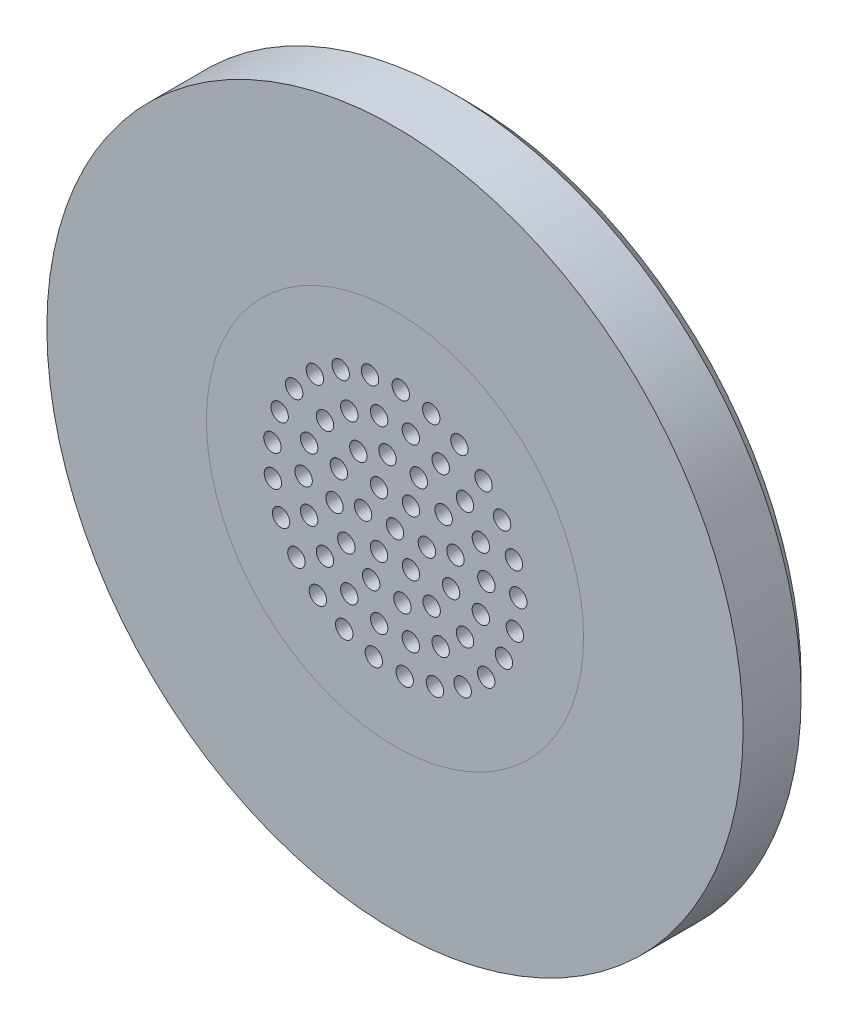
SolidWorks part; units mm, degrees
material "AISI 304"
ref_plane "Piano frontale" through (0, 0, 0) normal (0, 0, 1) x (1, 0, 0)
ref_plane "Piano superiore" through (0, 0, 0) normal (0, 1, 0) x (1, 0, 0)
ref_plane "Piano destro" through (0, 0, 0) normal (1, 0, 0) x (0, 0, -1)
sketch "Schizzo1" plane through (0, 0, 0) normal (0, 0, 1) x (1, 0, 0)
  line L0 (0, 0) -> (-24, 0) construction
  line L1 (0, 0) -> (-3.8661, 1.6411) construction
  line L2 (0, 0) -> (-8.4487, 0.9325) construction
  circle A0 centre (0, 0) radius 24
  circle A1 centre (-2.2, 0) radius 0.6
  circle A2 centre (0, 0) radius 2.2 construction
  circle A3 centre (0, 0) radius 4.2 construction
  circle A4 centre (0, 0) radius 0.6
  circle A5 centre (-3.8661, 1.6411) radius 0.6
  circle A6 centre (-1.1, 1.9053) radius 0.6
  circle A7 centre (1.1, 1.9053) radius 0.6
  circle A8 centre (2.2, 0) radius 0.6
  circle A9 centre (1.1, -1.9053) radius 0.6
  circle A10 centre (-1.1, -1.9053) radius 0.6
  circle A11 centre (-2.5276, 3.3543) radius 0.6
  circle A12 centre (-0.5119, 4.1687) radius 0.6
  circle A13 centre (1.6411, 3.8661) radius 0.6
  circle A14 centre (3.3543, 2.5276) radius 0.6
  circle A15 centre (4.1687, 0.5119) radius 0.6
  circle A16 centre (3.8661, -1.6411) radius 0.6
  circle A17 centre (2.5276, -3.3543) radius 0.6
  circle A18 centre (0.5119, -4.1687) radius 0.6
  circle A19 centre (-1.6411, -3.8661) radius 0.6
  circle A20 centre (-3.3543, -2.5276) radius 0.6
  circle A21 centre (-4.1687, -0.5119) radius 0.6
  circle A22 centre (0, 0) radius 6.3 construction
  circle A23 centre (-6.3, 0) radius 0.6
  circle A24 centre (-5.9201, 2.1547) radius 0.6
  circle A25 centre (-4.8261, 4.0496) radius 0.6
  circle A26 centre (-3.15, 5.456) radius 0.6
  circle A27 centre (-1.094, 6.2043) radius 0.6
  circle A28 centre (1.094, 6.2043) radius 0.6
  circle A29 centre (3.15, 5.456) radius 0.6
  circle A30 centre (4.8261, 4.0496) radius 0.6
  circle A31 centre (5.9201, 2.1547) radius 0.6
  circle A32 centre (6.3, 0) radius 0.6
  circle A33 centre (5.9201, -2.1547) radius 0.6
  circle A34 centre (4.8261, -4.0496) radius 0.6
  circle A35 centre (3.15, -5.456) radius 0.6
  circle A36 centre (1.094, -6.2043) radius 0.6
  circle A37 centre (-1.094, -6.2043) radius 0.6
  circle A38 centre (-3.15, -5.456) radius 0.6
  circle A39 centre (-4.8261, -4.0496) radius 0.6
  circle A40 centre (-5.9201, -2.1547) radius 0.6
  circle A43 centre (0, 0) radius 8.5 construction
  circle A44 centre (-8.4487, 0.9325) radius 0.6
  circle A45 centre (-7.9513, 3.0044) radius 0.6
  circle A46 centre (-6.9544, 4.8874) radius 0.6
  circle A47 centre (-5.5205, 6.4633) radius 0.6
  circle A48 centre (-3.7397, 7.6331) radius 0.6
  circle A49 centre (-1.7239, 8.3234) radius 0.6
  circle A50 centre (0.4002, 8.4906) radius 0.6
  circle A51 centre (2.4992, 8.1243) radius 0.6
  circle A52 centre (4.4411, 7.2475) radius 0.6
  circle A53 centre (6.1039, 5.9154) radius 0.6
  circle A54 centre (7.3833, 4.2116) radius 0.6
  circle A55 centre (8.1987, 2.2431) radius 0.6
  circle A56 centre (8.4989, 0.1337) radius 0.6
  circle A57 centre (8.2652, -1.9841) radius 0.6
  circle A58 centre (7.5121, -3.9772) radius 0.6
  circle A59 centre (6.287, -5.7205) radius 0.6
  circle A60 centre (4.6669, -7.1043) radius 0.6
  circle A61 centre (2.7535, -8.0417) radius 0.6
  circle A62 centre (0.6671, -8.4738) radius 0.6
  circle A63 centre (-1.4612, -8.3735) radius 0.6
  circle A64 centre (-3.4977, -7.747) radius 0.6
  circle A65 centre (-5.3144, -6.6338) radius 0.6
  circle A66 centre (-6.7972, -5.1037) radius 0.6
  circle A67 centre (-7.8529, -3.253) radius 0.6
  circle A68 centre (-8.4152, -1.1979) radius 0.6
  point P24 (0, 0)
  point P47 (0, 0)
  point P88 (0, 0)
  point P147 (0, 0)
  dimension "D1" = 1.2
  dimension "D3" = 4.4
  dimension "D4" = 8.4
  dimension "D5" = 6
  dimension "D7" = 12.6
  dimension "D10" = 17
  dimension "D11" = 48
  dimension "D2" = 23
  dimension "D6" = 12
  dimension "D8" = 18
  dimension "D9" = 25
extrude "Estrusione-Estrusione1" add sketch "Schizzo1" along normal blind 5
sketch "Schizzo4" plane through (0, 0, 5) normal (0, 0, 1) x (1, 0, 0)
  circle A0 centre (0, 0) radius 13
  dimension "D1" = 26
sketch "Schizzo5" plane through (0, 0, 0) normal (0, 0, -1) x (-1, 0, 0)
  circle A0 centre (0, 0) radius 13
  circle A1 centre (0, 0) radius 13 construction
split line "Linea di divisione1"
split line "Linea di divisione2"
chamfer "Smusso1" distance 1 angle 45 1 edges at (24, 0, 0)
chamfer "Smusso2" [suppressed] distance 1 angle 45
